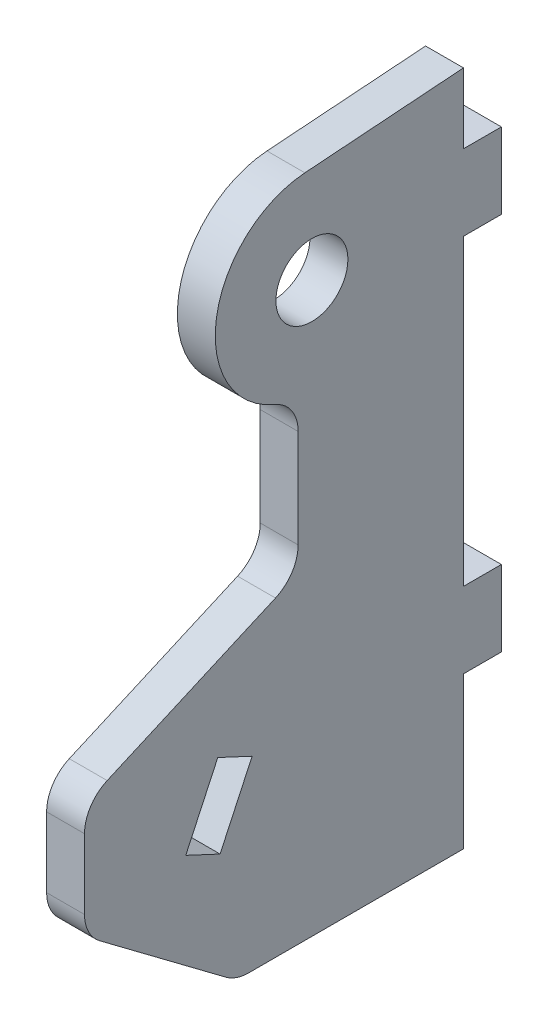
SolidWorks part; units mm, degrees
material "AISI 1020 Steel, Cold Rolled"
ref_plane "Front Plane" through (0, 0, 0) normal (1, 0, 0) x (0, 1, 0)
ref_plane "Top Plane" through (0, 0, 0) normal (0, 0, 1) x (0, 1, 0)
ref_plane "Right Plane" through (0, 0, 0) normal (0, 1, 0) x (-1, 0, 0)
sketch "Sketch1" plane through (0, 0, 0) normal (1, 0, 0) x (0, 1, 0)
  line L0 (-15.7577, 0) -> (-5, 0)
  line L1 (0, 0) -> (0, 20) construction
  line L2 (-15.7577, 0) -> (-12.6201, 21.8151) construction
  line L3 (14.2423, 0) -> (12.7162, 20.9273)
  line L4 (0, 0) -> (0, -5) construction
  line L5 (5, -5) -> (-5, -5)
  line L6 (-5, -5) -> (-5, 0)
  line L7 (5, -5) -> (5, 0)
  line L8 (5, 0) -> (14.2423, 0)
  line L9 (0, 0) -> (5, 0) construction
  line L10 (-5, 0) -> (0, 0) construction
  line L11 (0, 20) -> (0, 4.6155) construction
  line L12 (-15.7577, 0) -> (-74.9977, 0) construction
  line L13 (-74.9977, 0) -> (-74.9977, 50) construction
  line L14 (-74.9977, 50) -> (-44.9977, 50) construction
  line L15 (-44.9977, 50) -> (-32.6201, 21.8151)
  line L16 (-32.6201, 21.8151) -> (-12.6201, 21.8151) construction
  line L17 (-74.9977, 30) -> (-59.9977, 50)
  line L18 (-74.9977, 30) -> (-74.9977, 0)
  line L19 (-74.9977, 0) -> (-15.7577, 0)
  line L20 (-59.9977, 50) -> (-44.9977, 50)
  line L21 (-32.6201, 21.8151) -> (-12.6201, 21.8151)
  circle A0 centre (0, 20) radius 4.75
  arc A1 (12.7162, 20.9273) -> (-12.6201, 21.8151) centre (0, 20) ccw
  arc A2 (0, 7.25) -> (12.7162, 20.9273) centre (0, 20) ccw construction
  circle A3 centre (0, 20) radius 12.75 construction
  point P4 (0, 0)
  point P11 (12, 20)
  point P17 (0, -5)
  dimension "D3" = 9.5
  dimension "D4" = 8
  dimension "D1" = 30
  dimension "D2" = 20
  dimension "D5" = 5
  dimension "D6" = 10
  dimension "D7" = 15.3845
  dimension "D8" = 59.24
  dimension "D9" = 50
  dimension "D10" = 30
  dimension "D13" = 20
  dimension "D14" = 20
  dimension "D15" = 15
extrude "Boss-Extrude1" add sketch "Sketch1" along normal mid plane 5
fillet "Fillet1" radius 5 5 edges at (0, -12.6201, 21.8151) (0, -32.6201, 21.8151) (0, -74.9977, 30) (0, -59.9977, 50) (0, -44.9977, 50)
sketch "Sketch2" plane through (2.5, 0, 0) normal (1, 0, 0) x (0, 1, 0)
  line L0 (-74.9977, 0) -> (-54.9977, 0)
  line L1 (-74.9977, 0) -> (-5, 0) construction
  line L2 (-54.9977, 0) -> (-54.9977, 30)
  line L3 (-50.4662, 27.8869) -> (-59.5293, 32.1131)
  line L4 (-35.3557, 30) -> (-74.6397, 30) construction
  line L5 (-48.3531, 32.4184) -> (-57.4162, 36.6446)
  line L6 (-50.4662, 27.8869) -> (-48.3531, 32.4184)
  line L7 (-59.5293, 32.1131) -> (-57.4162, 36.6446)
  point P9 (-54.9977, 30)
  point P12 (-54.9977, 30)
  dimension "D1" = 20
  dimension "D2" = 30
  dimension "D3" = 10
  dimension "D4" = 25
  dimension "D5" = 5
extrude "Cut-Extrude1" cut sketch "Sketch2" against normal up to next contours L5 L7 L3 L6
sketch "Sketch3" plane through (0, 0, 0) normal (0, 0, -1) x (1, 0, 0)
  line L0 (2.5, 74.9977) -> (2.5, 55)
  line L1 (2.5, 74.9977) -> (2.5, 5) construction
  line L2 (-2.5, 74.9977) -> (-2.5, 5) construction
  line L3 (2.5, 55) -> (-2.5, 55)
  line L4 (2.5, 55) -> (2.5, 45)
  line L5 (2.5, 45) -> (-2.5, 45)
  line L6 (-2.5, 55) -> (-2.5, 45)
  line L7 (2.5, -5) -> (-2.5, -5) construction
  line M4 (-2.5, 74.9977) -> (-2.5, 5)
  line M6 (2.5, 5) -> (2.5, 74.9977)
  dimension "D1" = 60
  dimension "D2" = 10
extrude "Boss-Extrude2" add sketch "Sketch3" along normal blind 5 contours L5 L3 M6 M4
